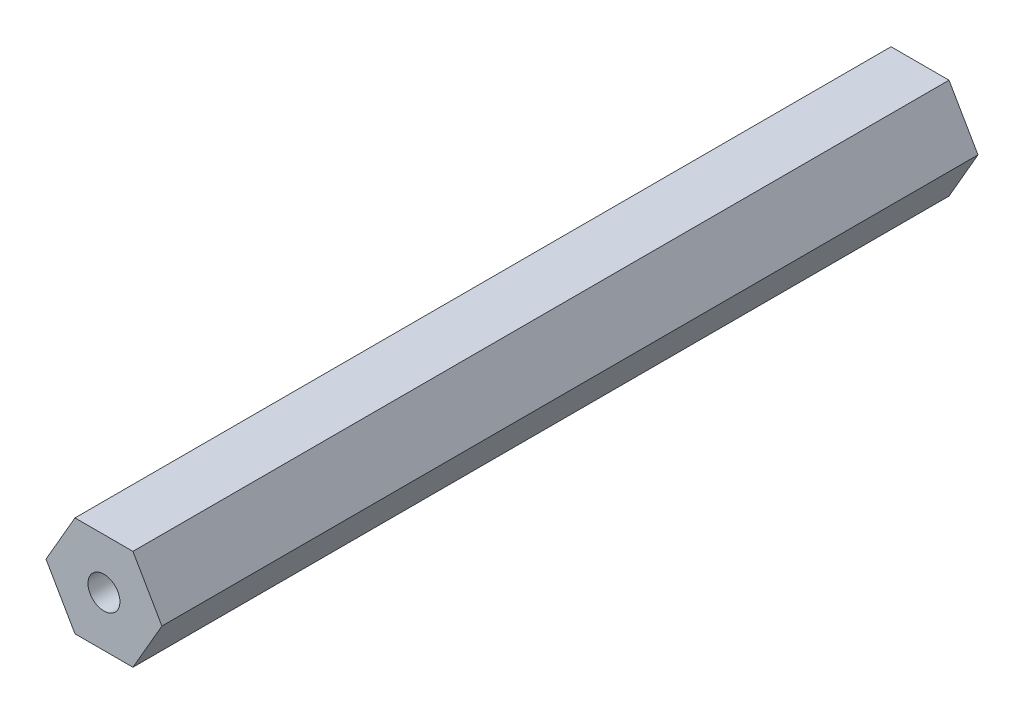
SolidWorks part; units mm, degrees
material "6061 Alloy"
ref_plane "Front Plane" through (0, 0, 0) normal (0, 0, 1) x (1, 0, 0)
ref_plane "Top Plane" through (0, 0, 0) normal (0, 1, 0) x (1, 0, 0)
ref_plane "Right Plane" through (0, 0, 0) normal (1, 0, 0) x (0, 0, -1)
sketch "Sketch1" plane through (0, 0, 0) normal (0, 0, 1) x (1, 0, 0)
  circle A0 centre (0, 0) radius 2.0193
  circle A1 centre (0, 0) radius 4.7625
  dimension "D1" = 9.525
  dimension "D2" = 4.0386
extrude "Boss-Extrude1" add sketch "Sketch1" along normal blind 103.251
sketch "Sketch2" plane through (0, 0, 103.251) normal (0, 0, 1) x (1, 0, 0)
  line L1 (7.3323, 0) -> (3.6662, 6.35)
  line L2 (3.6662, 6.35) -> (-3.6662, 6.35)
  line L3 (-3.6662, 6.35) -> (-7.3323, 0)
  line L4 (-7.3323, 0) -> (-3.6662, -6.35)
  line L5 (-3.6662, -6.35) -> (3.6662, -6.35)
  line L6 (3.6662, -6.35) -> (7.3323, 0)
  circle A0 centre (0, 0) radius 4.7625 construction
  circle A1 centre (0, 0) radius 4.7625
  circle A2 centre (0, 0) radius 6.35 construction
  dimension "D1" = 12.7
extrude "Boss-Extrude2" add sketch "Sketch2" against normal through all
